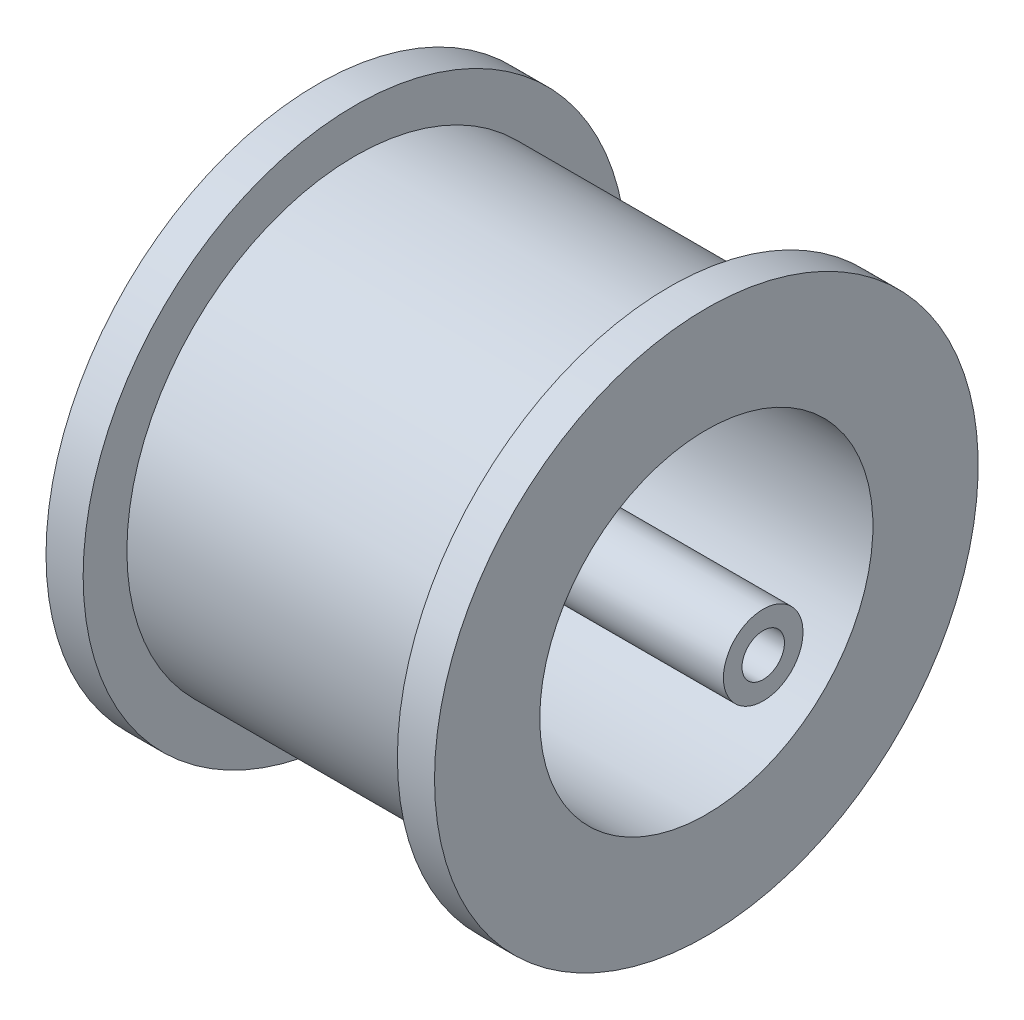
SolidWorks part; units mm, degrees
material "Alloy Steel"
ref_plane "Front Plane" through (0, 0, 0) normal (0, 0, 1) x (1, 0, 0)
ref_plane "Top Plane" through (0, 0, 0) normal (0, 1, 0) x (1, 0, 0)
ref_plane "Right Plane" through (0, 0, 0) normal (1, 0, 0) x (0, 0, -1)
sketch "Sketch1" plane through (0, 0, 0) normal (0, 0, 1) x (1, 0, 0)
  line L0 (0, 0) -> (10.4339, 0) construction
  line L1 (0, 10.25) -> (0, 6.5)
  line L2 (0, 6.5) -> (2.6, 6.5)
  line L3 (2.6, 6.5) -> (2.6, 5)
  line L4 (2.6, 5) -> (4.6, 5)
  line L5 (4.6, 5) -> (4.6, 6.2814)
  line L6 (4.6, 6.2814) -> (14.65, 6.2814)
  line L7 (14.65, 6.2814) -> (14.65, 10.25)
  line L8 (14.65, 10.25) -> (13.25, 10.25)
  line L9 (13.25, 10.25) -> (13.25, 8.6)
  line L10 (13.25, 8.6) -> (1.4, 8.6)
  line L11 (1.4, 8.6) -> (1.4, 10.25)
  line L12 (1.4, 10.25) -> (0, 10.25)
  dimension "D1" = 2.6
  dimension "D2" = 2
  dimension "D3" = 14.65
  dimension "D4" = 1.4
  dimension "D5" = 1.4
  dimension "D6" = 5
  dimension "D7" = 6.5
  dimension "D8" = 8.6
  dimension "D9" = 10.25
revolve "Revolve1" add sketch "Sketch1" angle 360 about L0
sketch "Sketch3" plane through (0, 0, 0) normal (0, 0, 1) x (1, 0, 0)
  line L0 (0, 0) -> (25.177, 0) construction
  line L1 (1.0943, 0) -> (1.0943, 3.7629)
  line L2 (1.0943, 0) -> (16.7943, 0)
  line L3 (16.7943, 0) -> (16.7943, 1.5)
  line L4 (16.7943, 1.5) -> (5.0138, 1.5)
  line L5 (5.0138, 1.5) -> (1.0943, 3.7629)
  dimension "D1" = 15.7
  dimension "D2" = 1.5
  dimension "D3" = 3.7629
  dimension "D4" = 60
revolve "Revolve2" add sketch "Sketch3" angle 360 about L0
sketch "Sketch6" plane through (16.7943, 0, 0) normal (1, 0, 0) x (0, 0, -1)
  circle A0 centre (0, 0) radius 0.8
  circle A1 centre (0, 0) radius 10.25 construction
extrude "Cut-Extrude1" cut sketch "Sketch6" against normal blind 10
sketch "Sketch8" plane through (0, 0, 0) normal (0, 0, 1) x (1, 0, 0)
  line L0 (0, 0) -> (26.5992, 0) construction
  line L1 (0, 0) -> (0, 5)
  line L2 (0, 6.5) -> (0, -6.5) construction
  line L3 (0, 5) -> (2.6, 6.5)
  line L4 (2.6, 6.5) -> (2.6, -6.5) construction
  line L5 (0, 0) -> (1.0943, 0)
  line L6 (1.0943, 3.7629) -> (1.0943, -3.7629) construction
  line L7 (1.0943, 0) -> (1.0943, 3.8547)
  line L8 (2.6, 6.5) -> (2.6, 4.724)
  line L10 (2.6, 4.724) -> (1.0943, 3.8547)
  point P19 (2.6712, 4.7651)
  dimension "D1" = 5
  dimension "D2" = 120
  dimension "D3" = 6.5
revolve "Revolve3" add sketch "Sketch8" angle 360 about L0
sketch "Sketch9" plane through (0, 0, 0) normal (-1, 0, 0) x (0, 0, 1)
  line L0 (0, 0) -> (0, 5) construction
  line L1 (1.061, 2) -> (-1.061, 2)
  line L2 (-1.061, 2) -> (-2.8114, 4.0861)
  line L3 (1.061, 2) -> (2.8114, 4.0861)
  line L4 (2, 1.061) -> (4.0861, 2.8114)
  line L5 (2, -1.061) -> (2, 1.061)
  line L6 (2, -1.061) -> (4.0861, -2.8114)
  line L7 (1.061, -2) -> (2.8114, -4.0861)
  line L8 (-1.061, -2) -> (1.061, -2)
  line L9 (-1.061, -2) -> (-2.8114, -4.0861)
  line L10 (-2, -1.061) -> (-4.0861, -2.8114)
  line L11 (-2, 1.061) -> (-2, -1.061)
  line L12 (-2, 1.061) -> (-4.0861, 2.8114)
  circle A0 centre (0, 0) radius 5 construction
  arc A1 (2.8114, 4.0861) -> (-2.8114, 4.0861) centre (0, 0) ccw
  arc A2 (4.0861, -2.8114) -> (4.0861, 2.8114) centre (0, 0) ccw
  arc A3 (-2.8114, -4.0861) -> (2.8114, -4.0861) centre (0, 0) ccw
  arc A4 (-4.0861, 2.8114) -> (-4.0861, -2.8114) centre (0, 0) ccw
  point P11 (0, 2)
  point P26 (0, 0)
  dimension "D1" = 130
  dimension "D2" = 2
  dimension "D3" = 4
extrude "Cut-Extrude2" cut sketch "Sketch9" against normal blind 10
